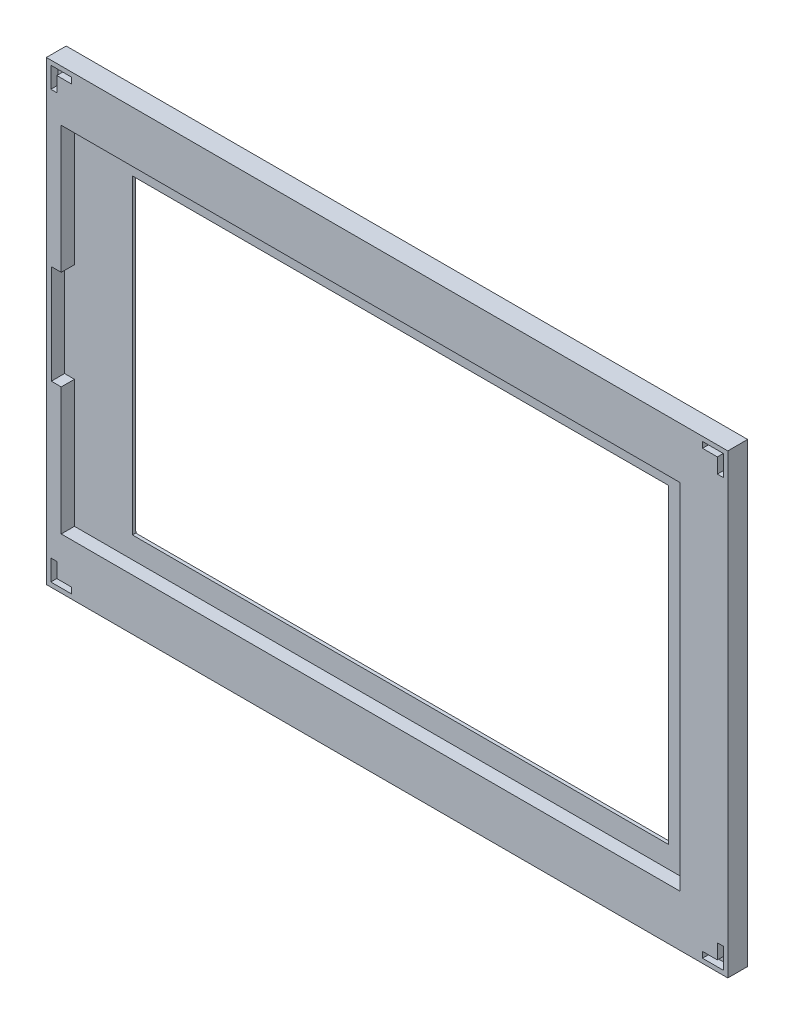
SolidWorks part; units mm, degrees
ref_plane "Front Plane" through (0, 0, 0) normal (0, 0, 1) x (1, 0, 0)
ref_plane "Top Plane" through (0, 0, 0) normal (0, 1, 0) x (1, 0, 0)
ref_plane "Right Plane" through (0, 0, 0) normal (1, 0, 0) x (0, 0, -1)
sketch "Sketch1" plane through (0, 0, 0) normal (0, 0, 1) x (1, 0, 0)
  line L1 (113.8284, 62.9439) -> (10.8284, 62.9439)
  line L2 (113.8284, 62.9439) -> (113.8284, -6.0561)
  line L3 (113.8284, -6.0561) -> (10.8284, -6.0561)
  line L4 (10.8284, 62.9439) -> (10.8284, -6.0561)
  dimension "D1" = 69
  dimension "D2" = 103
extrude "Boss-Extrude1" add sketch "Sketch1" along normal blind 3
sketch "Sketch2" plane through (0, 0, 3) normal (0, 0, 1) x (1, 0, 0)
  line L0 (10.8284, 62.9439) -> (10.8284, -6.0561) construction
  line L1 (21.8284, 51.9439) -> (102.8284, 51.9439)
  line L2 (21.8284, 51.9439) -> (21.8284, 4.9439)
  line L3 (21.8284, 4.9439) -> (102.8284, 4.9439)
  line L4 (102.8284, 51.9439) -> (102.8284, 4.9439)
  line L5 (113.8284, 62.9439) -> (10.8284, 62.9439) construction
  line L6 (113.8284, -6.0561) -> (113.8284, 62.9439) construction
  line L7 (10.8284, -6.0561) -> (113.8284, -6.0561) construction
  dimension "D1" = 11
  dimension "D2" = 11
  dimension "D3" = 11
  dimension "D4" = 11
extrude "Cut-Extrude1" cut sketch "Sketch2" against normal blind 3
sketch "Sketch3" plane through (0, 0, 3) normal (0, 0, 1) x (1, 0, 0)
  line L0 (113.8284, -6.0561) -> (113.8284, 62.9439) construction
  line L1 (13.0784, 55.1939) -> (106.5784, 55.1939)
  line L2 (13.0784, 55.1939) -> (13.0784, 35.9439)
  line L3 (13.0784, 1.6939) -> (106.5784, 1.6939)
  line L11 (106.5784, 55.1939) -> (106.5784, 1.6939)
  line L12 (13.0784, 20.9439) -> (13.0784, 1.6939)
  line L13 (13.0784, 35.9439) -> (11.5784, 35.9439)
  line L15 (13.0784, 20.9439) -> (11.5784, 20.9439)
  line L16 (11.5784, 35.9439) -> (11.5784, 20.9439)
  line L18 (21.8284, 51.9439) -> (21.8284, 4.9439) construction
  point P13 (113.8284, 28.4439)
  point P14 (106.5784, 28.4439)
  dimension "D1" = 93.5
  dimension "D2" = 53.5
  dimension "D3" = 8.75
  dimension "D4" = 1.5
  dimension "D5" = 15
  dimension "D6" = 19.25
extrude "Cut-Extrude2" cut sketch "Sketch3" against normal blind 2
chamfer "Chamfer1" distance 0.5 angle 45 4 edges at (62.3284, 4.9439, 0) (102.8284, 28.4439, 0) (62.3284, 51.9439, 0) (21.8284, 28.4439, 0)
fillet "Fillet1" radius 0.5 4 edges at (21.5784, 52.1939, 0.25) (21.5784, 4.6939, 0.25) (103.0784, 4.6939, 0.25) (103.0784, 52.1939, 0.25)
sketch "Sketch4" plane through (0, 0, 3) normal (0, 0, 1) x (1, 0, 0)
  line L6 (11.5034, 62.2689) -> (14.6534, 62.2689)
  line L7 (14.6534, 62.2689) -> (14.6534, 61.3689)
  line L8 (14.6534, 61.3689) -> (12.4034, 61.3689)
  line L9 (12.4034, 61.3689) -> (12.4034, 59.1189)
  line L10 (12.4034, 59.1189) -> (11.5034, 59.1189)
  line L11 (11.5034, 59.1189) -> (11.5034, 62.2689)
  line L12 (62.3284, 62.9439) -> (62.3284, 70.0431) construction
  line L13 (113.8284, 62.9439) -> (10.8284, 62.9439) construction
  line L14 (10.8284, 28.4439) -> (2.7952, 28.4439) construction
  line L15 (10.8284, 62.9439) -> (10.8284, -6.0561) construction
  line L16 (113.1534, 59.1189) -> (113.1534, 62.2689)
  line L17 (112.2534, 59.1189) -> (113.1534, 59.1189)
  line L18 (112.2534, 61.3689) -> (112.2534, 59.1189)
  line L19 (110.0034, 61.3689) -> (112.2534, 61.3689)
  line L20 (110.0034, 62.2689) -> (110.0034, 61.3689)
  line L21 (113.1534, 62.2689) -> (110.0034, 62.2689)
  line L22 (113.1534, -5.3811) -> (110.0034, -5.3811)
  line L23 (110.0034, -5.3811) -> (110.0034, -4.4811)
  line L24 (110.0034, -4.4811) -> (112.2534, -4.4811)
  line L25 (112.2534, -4.4811) -> (112.2534, -2.2311)
  line L26 (112.2534, -2.2311) -> (113.1534, -2.2311)
  line L27 (113.1534, -2.2311) -> (113.1534, -5.3811)
  line L28 (11.5034, -2.2311) -> (11.5034, -5.3811)
  line L29 (12.4034, -2.2311) -> (11.5034, -2.2311)
  line L30 (12.4034, -4.4811) -> (12.4034, -2.2311)
  line L31 (14.6534, -4.4811) -> (12.4034, -4.4811)
  line L32 (14.6534, -5.3811) -> (14.6534, -4.4811)
  line L33 (11.5034, -5.3811) -> (14.6534, -5.3811)
extrude "Cut-Extrude3" cut sketch "Sketch4" against normal blind 1.1
